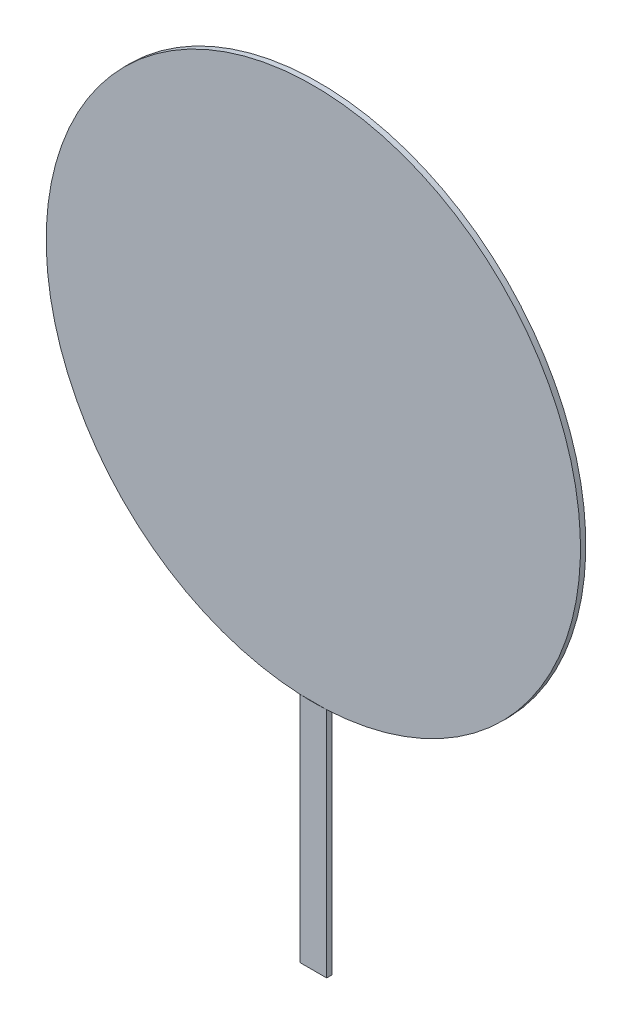
SolidWorks part; units mm, degrees
ref_plane "前视基准面" through (0, 0, 0) normal (0, 0, 1) x (1, 0, 0)
ref_plane "上视基准面" through (0, 0, 0) normal (0, 1, 0) x (1, 0, 0)
ref_plane "右视基准面" through (0, 0, 0) normal (1, 0, 0) x (0, 0, -1)
sketch "草图1" plane through (0, 0, 0) normal (0, 0, 1) x (1, 0, 0)
  line L5 (-5.0009, -99.8727) -> (4.9991, -99.8727)
  line L10 (-5.0009, -99.8727) -> (-5.0009, -186.8476)
  line L11 (-5.0009, -186.8476) -> (4.9991, -186.8476)
  line L16 (4.9991, -99.8727) -> (4.9991, -186.8476)
  circle A0 centre (0, 0) radius 100
  point P3 (5.7986, 0)
  point P5 (0, 0)
extrude "凸台-拉伸2" add sketch "草图1" along normal blind 2 contours A0 L10 L11 L16 | L16 A0 L10 L5
